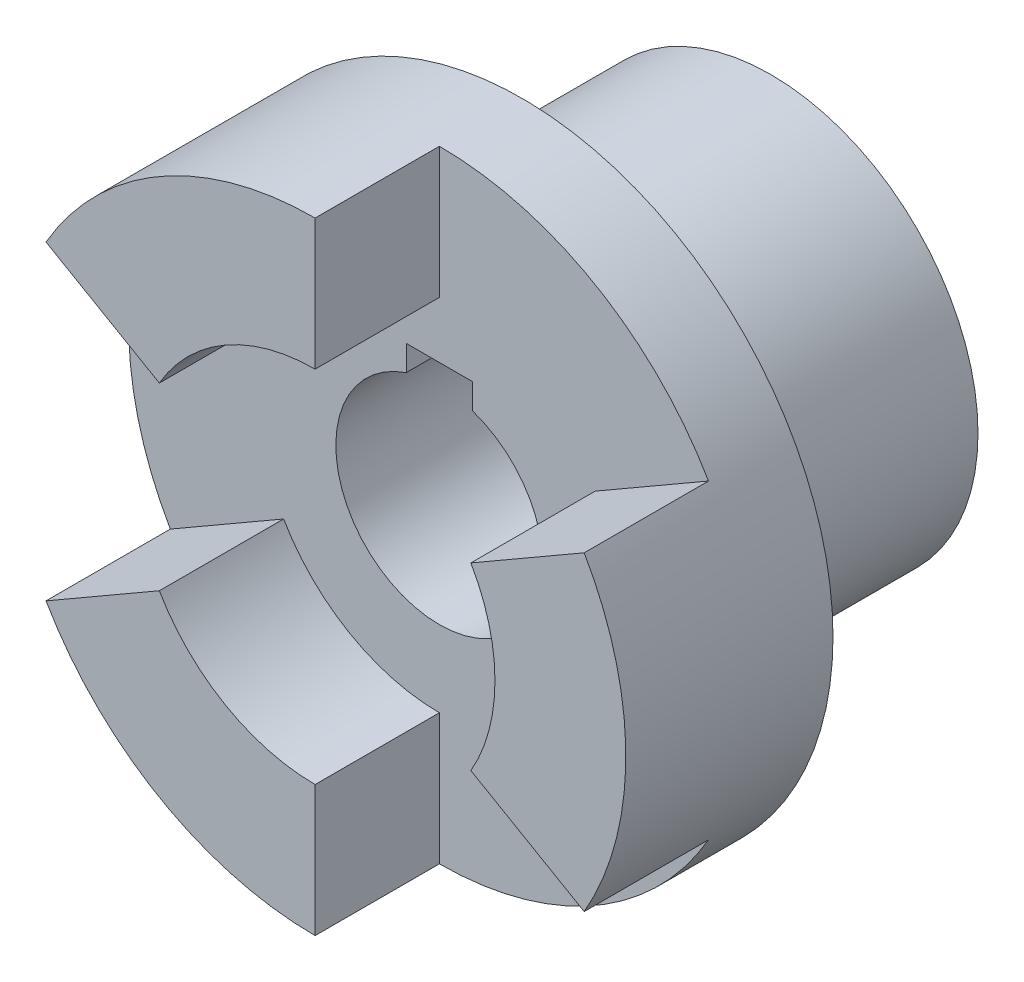
SolidWorks part; units mm, degrees
ref_plane "Front Plane" through (0, 0, 0) normal (0, 0, 1) x (1, 0, 0)
ref_plane "Top Plane" through (0, 0, 0) normal (0, 1, 0) x (1, 0, 0)
ref_plane "Right Plane" through (0, 0, 0) normal (1, 0, 0) x (0, 0, -1)
sketch "Sketch1" plane through (0, 0, 0) normal (0, 0, 1) x (1, 0, 0)
  line L0 (0, 0) -> (32604.7089, 0) construction
  line L1 (0, 0) -> (0, 32604.7089) construction
  circle A0 centre (0, 0) radius 37.5
  arc A1 (-4, 11.8427) -> (4, 11.8427) centre (0, 0) ccw
  arc A2 (-4, 11.8427) -> (4, 11.8427) centre (0, 0) cw
  dimension "D1" = 75
  dimension "D4" = 25
extrude "Boss-Extrude1" add sketch "Sketch1" along normal blind 10
sketch "Sketch3" plane through (0, 0, 10) normal (0, 0, 1) x (1, 0, 0)
  line L0 (-32.476, -18.75) -> (-18.7984, -10.8532)
  line L1 (0, -37.5) -> (0, -21.7065)
  line L2 (0, 0) -> (0, 50000) construction
  line L3 (0, 37.5) -> (0, 21.7065)
  line L4 (-32.476, 18.75) -> (-18.7984, 10.8532)
  line L5 (32.476, -18.75) -> (18.7984, -10.8532)
  line L6 (32.476, 18.75) -> (18.7984, 10.8532)
  circle A0 centre (0, 0) radius 21.7065 construction
  circle A1 centre (0, 0) radius 37.5 construction
  arc A2 (-32.476, -18.75) -> (0, -37.5) centre (0, 0) ccw
  arc A3 (-18.7984, -10.8532) -> (0, -21.7065) centre (0, 0) ccw
  arc A4 (0, 21.7065) -> (-18.7984, 10.8532) centre (0, 0) ccw
  arc A5 (0, 37.5) -> (-32.476, 18.75) centre (0, 0) ccw
  arc A6 (18.7984, -10.8532) -> (18.7984, 10.8532) centre (0, 0) ccw
  arc A7 (32.476, -18.75) -> (32.476, 18.75) centre (0, 0) ccw
  point P9 (0, 0)
  point P27 (0, 0)
  dimension "D2" = 43.413
  dimension "D1" = 60
  dimension "D3" = 3
extrude "Boss-Extrude2" add sketch "Sketch3" along normal blind 15 contours A6 L5 A5 L6 | A3 L0 A5 L1
sketch "Sketch5" plane through (0, 0, 0) normal (0, 0, -1) x (-1, 0, 0)
  circle A0 centre (0, 0) radius 25
  circle A1 centre (0, 0) radius 12.5 construction
  circle A2 centre (0, 0) radius 12.5
  dimension "D1" = 50
extrude "Boss-Extrude3" add sketch "Sketch5" along normal blind 30
sketch "Sketch7" plane through (0, 0, 0) normal (1, 0, 0) x (0, 0, -1)
  line L0 (30, 0) -> (-10, 0)
  line L1 (30, -12.5) -> (30, 12.5) construction
  line L2 (-10, 0) -> (-10, 14.9)
  line L4 (-10, 14.9) -> (30, 14.5)
  line L5 (30, -25) -> (30, 25) construction
  line L6 (30, 14.5) -> (30, 0)
  point P6 (-9.666, 0)
  dimension "D1" = 14.9
  dimension "D2" = 14.5
  dimension "D3" = 40
extrude "Cut-Extrude1" cut sketch "Sketch7" against normal mid plane 8
